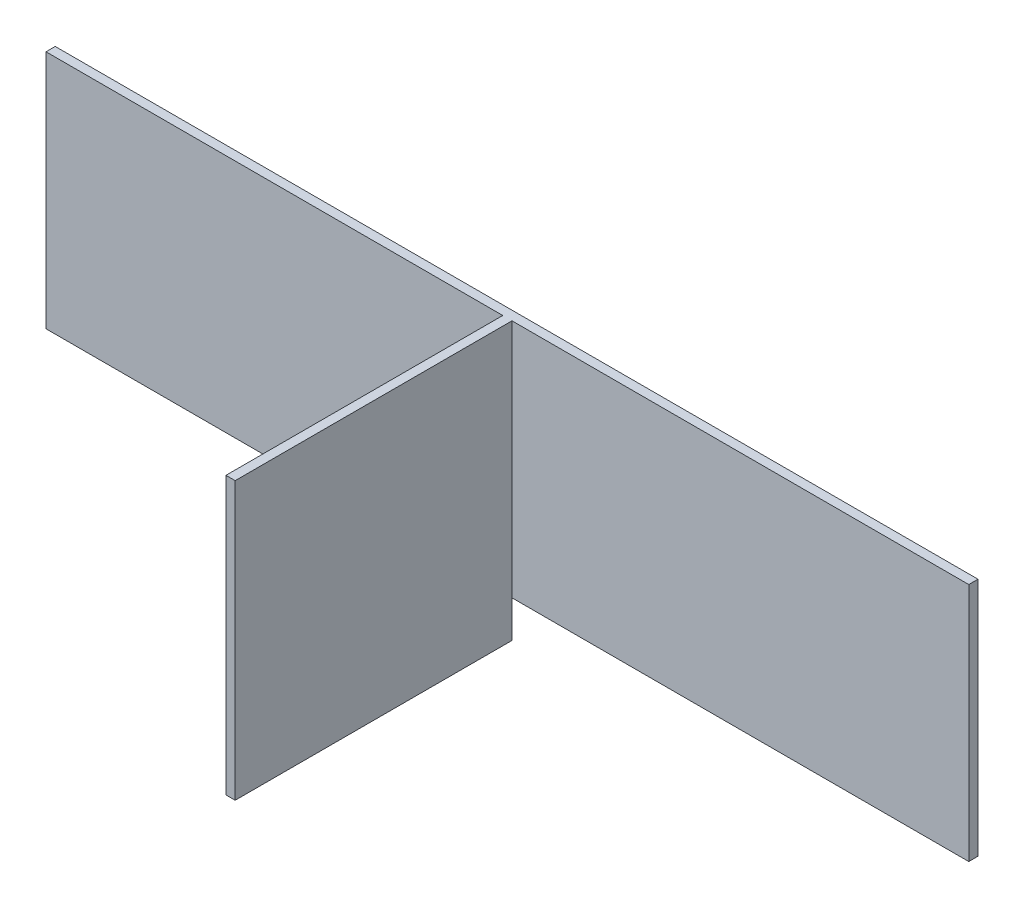
SolidWorks part; units mm, degrees
ref_plane "Front Plane" through (0, 0, 0) normal (0, 0, 1) x (1, 0, 0)
ref_plane "Top Plane" through (0, 0, 0) normal (0, 1, 0) x (1, 0, 0)
ref_plane "Right Plane" through (0, 0, 0) normal (1, 0, 0) x (0, 0, -1)
sketch "Sketch1" plane through (0, 0, 0) normal (0, 0, 1) x (1, 0, 0)
  line L1 (250, -65) -> (250, 65)
  line L2 (250, 65) -> (-250, 65)
  line L3 (-250, 65) -> (-250, -65)
  line L4 (-250, -65) -> (250, -65)
  dimension "D1" = 500
  dimension "D2" = 130
extrude "Boss-Extrude1" add sketch "Sketch1" along normal blind 5
sketch "Sketch2" plane through (0, 0, 5) normal (0, 0, 1) x (1, 0, 0)
  line L0 (0, 65) -> (0, -65) construction
  line L1 (250, 65) -> (-250, 65) construction
  line L2 (-250, -65) -> (250, -65) construction
  line L3 (-2.5, -65) -> (2.5, -65)
  line L4 (2.5, -65) -> (2.5, 65)
  line L5 (2.5, 65) -> (-2.5, 65)
  line L6 (-2.5, 65) -> (-2.5, -65)
  dimension "D1" = 5
extrude "Boss-Extrude2" add sketch "Sketch2" along normal blind 150 contours L6 L3 L4 L5
sketch "Sketch3" plane through (0, -65, 0) normal (0, -1, 0) x (-1, 0, 0)
  line L0 (-2.5, -155) -> (-2.5, -5)
  line L1 (-2.5, -5) -> (2.5, -5)
  line L2 (2.5, -5) -> (2.5, -155)
  line L3 (2.5, -155) -> (-2.5, -155)
extrude "Boss-Extrude3" add sketch "Sketch3" along normal blind 20 contours L3 L0 L1 L2
